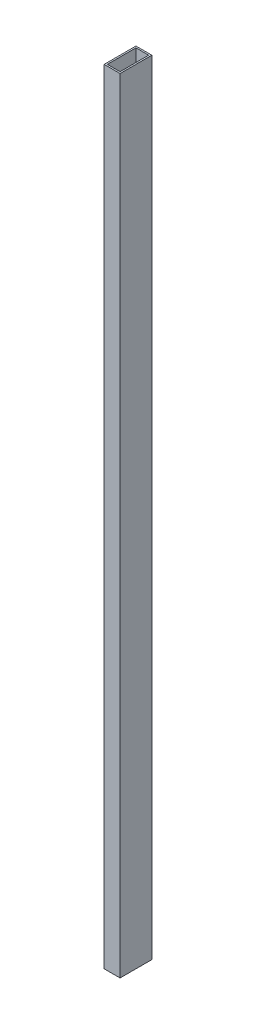
SolidWorks part; units mm, degrees
material "Acero al carbono no aleado"
ref_plane "Alzado" through (0, 0, 0) normal (0, 0, 1) x (1, 0, 0)
ref_plane "Planta" through (0, 0, 0) normal (0, 1, 0) x (1, 0, 0)
ref_plane "Vista lateral" through (0, 0, 0) normal (1, 0, 0) x (0, 0, -1)
sketch "Croquis1" plane through (0, 0, 0) normal (1, 0, 0) x (0, 0, -1)
  line L1 (0, 0) -> (-40, 0)
  line L2 (0, 0) -> (0, 985.51)
  line L3 (0, 985.51) -> (-40, 985.51)
  line L4 (-40, 0) -> (-40, 985.51)
  dimension "D1" = 985.51
  dimension "D2" = 40
extrude "Saliente-Extruir1" add sketch "Croquis1" along normal blind 20
sketch "Croquis2" plane through (0, 985.51, 0) normal (0, 1, 0) x (1, 0, 0)
  line L0 (20, -40) -> (0, -40) construction
  line L1 (2, -2) -> (18, -2)
  line L2 (2, -2) -> (2, -38)
  line L3 (2, -38) -> (18, -38)
  line L4 (18, -2) -> (18, -38)
  line L5 (2, -2) -> (18, -38) construction
  line L6 (2, -38) -> (18, -2) construction
  line L7 (20, 0) -> (0, 0) construction
  line L8 (0, 0) -> (0, -40) construction
  line L9 (20, 0) -> (20, -40) construction
  point P0 (10, -20)
  dimension "D1" = 2
  dimension "D2" = 2
  dimension "D3" = 2
  dimension "D4" = 2
extrude "Cortar-Extruir1" cut sketch "Croquis2" against normal blind 1000
